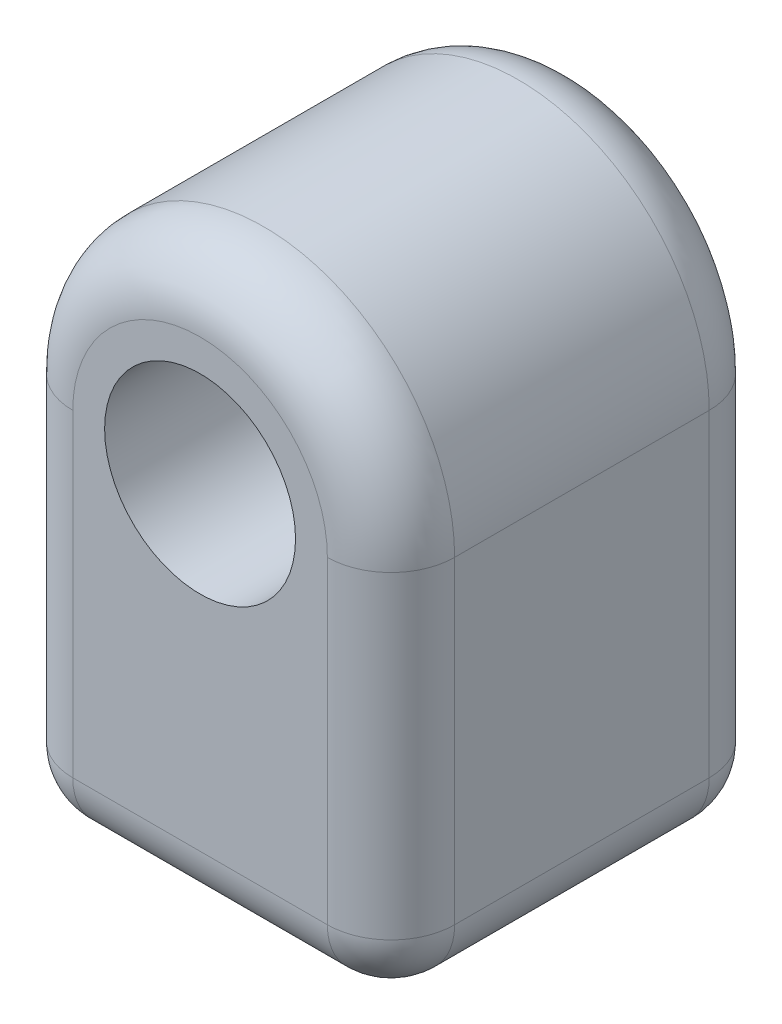
SolidWorks part; units mm, degrees
ref_plane "Alzado" through (0, 0, 0) normal (0, 0, 1) x (1, 0, 0)
ref_plane "Planta" through (0, 0, 0) normal (0, 1, 0) x (1, 0, 0)
ref_plane "Vista lateral" through (0, 0, 0) normal (1, 0, 0) x (0, 0, -1)
sketch "Croquis1" plane through (0, 0, 0) normal (0, 0, 1) x (1, 0, 0)
  line L0 (-3, 0) -> (-3, -6)
  line L1 (-3, -6) -> (3, -6)
  line L2 (3, -6) -> (3, 0)
  circle A0 centre (0, 0) radius 1.5
  arc A1 (3, 0) -> (-3, 0) centre (0, 0) ccw
  dimension "D1" = 3
  dimension "D2" = 3
  dimension "D3" = 6
extrude "Saliente-Extruir1" add sketch "Croquis1" along normal blind 6
sketch "Croquis3" plane through (-3, 0, 0) normal (-1, 0, 0) x (0, 0, 1)
  line L0 (0, -6) -> (3.344, -9.344) construction
  line L1 (6, -6) -> (0, -6) construction
  dimension "D1" = 45
sketch "Croquis2" plane through (0, 0, 0) normal (0, 0, -1) x (-1, 0, 0)
  line L0 (3, 0) -> (3, -6) construction
  line L1 (-1.25, -2) -> (1.25, -2)
  line L2 (-1.25, -2) -> (-1.25, -3.5)
  line L3 (-1.25, -3.5) -> (1.25, -3.5)
  line L4 (1.25, -2) -> (1.25, -3.5)
  line L6 (3, -6) -> (-3, -6) construction
  dimension "D1" = 1.5
  dimension "D2" = 2.5
  dimension "D3" = 1.75
  dimension "D4" = 2.5
extrude "Cortar-Extruir1" cut sketch "Croquis2" along direction (0, -0.7071, 0.7071) on the side against the normal blind 6
fillet "Redondeo3" radius 1 10 edges at (0, 3, 0) (0, 3, 6) (3, -3, 0) (0, -6, 0) (-3, -3, 0) (-3, -3, 6) (3, -3, 6) (3, -6, 3) (-3, -6, 3) (0, -6, 6)
